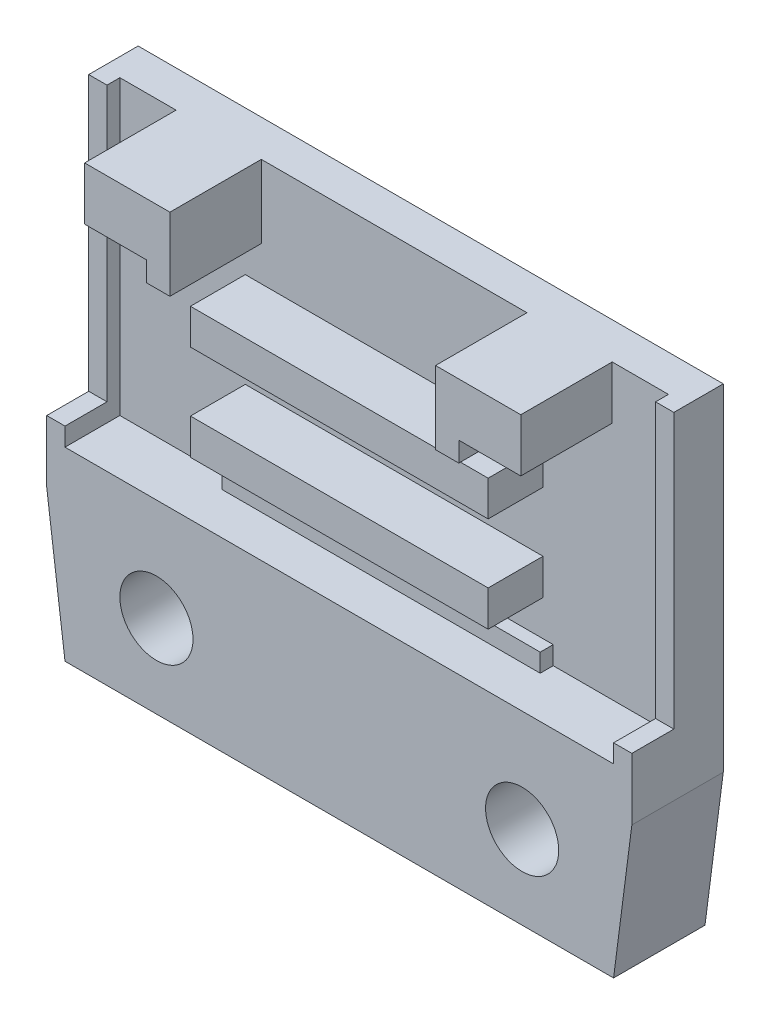
SolidWorks part; units mm, degrees
ref_plane "前视基准面" through (0, 0, 0) normal (0, 0, 1) x (1, 0, 0)
ref_plane "上视基准面" through (0, 0, 0) normal (0, 1, 0) x (1, 0, 0)
ref_plane "右视基准面" through (0, 0, 0) normal (1, 0, 0) x (0, 0, -1)
other "Configuration Table"
sketch "草图1" plane through (0, 0, 0) normal (0, 0, 1) x (1, 0, 0)
  line L1 (0, 0) -> (30, 0)
  line L2 (0, 0) -> (0, 15)
  line L3 (0, 15) -> (30, 15)
  line L4 (30, 0) -> (30, 15)
  dimension "D1" = 30
  dimension "D2" = 15
extrude "凸台-拉伸1" add sketch "草图1" along normal mid plane 2
sketch "草图2" plane through (0, 0, 1) normal (0, 0, 1) x (1, 0, 0)
  line L0 (25, 0) -> (25, -6.6)
  line L1 (0, 0) -> (30, 0) construction
  line L2 (30, 0) -> (30, 15) construction
  line L3 (30, 0) -> (30, -11.1397)
  line L4 (30, -11.1397) -> (0, -11.1397)
  line L5 (0, -11.1397) -> (0, 0)
  line L6 (15, -11.1397) -> (15, -4.661) construction
  line L7 (0, 0) -> (30, 0)
  circle A0 centre (25, -6.6) radius 2
  circle A1 centre (5, -6.6) radius 2
  dimension "D3" = 4
  dimension "D1" = 6.6
  dimension "D2" = 5
extrude "凸台-拉伸2" add sketch "草图2" along normal blind 3 and the other way blind 2
sketch "草图3" plane through (0, 0, 4) normal (0, 0, 1) x (1, 0, 0)
  line L0 (23.7, -1) -> (23.7, 0)
  line L1 (0, 0) -> (30, 0) construction
  line L2 (23.7, -1) -> (30, -1)
  line L3 (30, 0) -> (30, -11.1397) construction
  line L5 (23.7, 0) -> (30, 0)
  line L6 (30, 0) -> (30, -1)
  line L7 (15, 0) -> (15, 5.0746) construction
  line L8 (0, 0) -> (0, -1)
  line L9 (6.3, 0) -> (0, 0)
  line L10 (6.3, -1) -> (0, -1)
  line L11 (6.3, -1) -> (6.3, 0)
  dimension "D1" = 1
  dimension "D2" = 6.3
extrude "切除-拉伸1" cut sketch "草图3" against normal blind 3
sketch "草图4" plane through (30, 0, 0) normal (1, 0, 0) x (0, 0, -1)
  line L2 (-1.704, 0) -> (-1.704, 15)
  line L3 (-1.704, 15) -> (-1, 15)
  line L4 (-1, 15) -> (1, 15)
  line L5 (1, 15) -> (1, -3.391)
  line L6 (1, -11.1397) -> (1, 15) construction
  line L7 (1, -3.391) -> (-4, -3.391)
  line L8 (-4, -1) -> (-4, -11.1397) construction
  line L9 (-4, -3.391) -> (-4, 0)
  line L10 (-4, 0) -> (-1.704, 0)
  line L11 (-1, 0) -> (-4, 0) construction
extrude "凸台-拉伸3" add sketch "草图4" along normal blind 1
ref_plane "基准面1" through (15, 0, 0) normal (1, 0, 0) x (0, 0, -1)
sketch "草图5" plane through (0, 0, 4) normal (0, 0, 1) x (1, 0, 0)
  line L0 (31, -3.391) -> (30, -11.1397)
  line L1 (30, -11.1397) -> (30, -3.391)
  line L2 (30, -3.391) -> (31, -3.391)
extrude "凸台-拉伸4" add sketch "草图5" along direction (0, 0, -1) on the side against the normal up to surface (5 mm away)
mirror "镜向1" about plane through (15, 0, 0) normal (1, 0, 0) of "凸台-拉伸4", "凸台-拉伸3"
sketch "草图8" plane through (6.3, 0, 0) normal (-1, 0, 0) x (0, 0, 1)
  line L0 (1.7119, 0) -> (1.7119, -1)
  line L1 (1, 0) -> (4, 0) construction
  line L2 (1, -1) -> (4, -1) construction
  line L3 (1.7119, -1) -> (4, -1)
  line L4 (4, -1) -> (4, 0)
  line L5 (4, 0) -> (1.7119, 0)
extrude "切除-拉伸2" cut sketch "草图8" against normal up to next
sketch "草图9" plane through (0, 0, 1) normal (0, 0, 1) x (1, 0, 0)
  line L0 (3.0739, 15) -> (6.1478, 15)
  line L1 (30, 15) -> (0, 15) construction
  line L4 (3.0739, 11.937) -> (6.1478, 11.937)
  line L6 (15, 15) -> (15, 18.7793) construction
  line L12 (3.0739, 11.937) -> (3.0739, 15)
  line L13 (22.2627, 15) -> (23.8522, 15)
  line L14 (6.1478, 11.937) -> (6.2463, 11.937)
  line L15 (6.2463, 11.937) -> (6.2463, 11.0133)
  line L16 (6.2463, 11.0133) -> (7.7373, 11.0133)
  line L17 (7.7373, 11.0133) -> (7.7373, 15)
  line L18 (7.7373, 15) -> (6.1478, 15)
  line L19 (7.7373, 15) -> (6.1478, 15)
  line L20 (22.2627, 15) -> (23.8522, 15)
  line L21 (22.2627, 11.0133) -> (22.2627, 15)
  line L22 (23.7537, 11.0133) -> (22.2627, 11.0133)
  line L23 (23.7537, 11.937) -> (23.7537, 11.0133)
  line L24 (23.8522, 11.937) -> (23.7537, 11.937)
  line L25 (26.9261, 11.937) -> (26.9261, 15)
  line L26 (26.9261, 11.937) -> (23.8522, 11.937)
  line L27 (26.9261, 15) -> (23.8522, 15)
  line M19 (30, 15) -> (0, 15)
extrude "凸台-拉伸6" add sketch "草图9" along normal blind 5 contours L16 L17 L12 L4 L14 L15 M19 | L26 L25 L21 L22 L23 L24 M19
sketch "草图10" plane through (0, 0, 1) normal (0, 0, 1) x (1, 0, 0)
  line L0 (6.86, 1.9479) -> (23.14, 1.9479)
  line L1 (6.86, 3.9045) -> (23.14, 3.9045)
  line L2 (6.86, 7.1707) -> (23.14, 7.1707)
  line L3 (6.86, 9.1033) -> (23.14, 9.1033)
  line L4 (6.86, 9.1033) -> (6.86, 7.1707)
  line L5 (15, 9.1033) -> (15, 12.3733) construction
  line L6 (23.14, 9.1033) -> (23.14, 7.1707)
  line L7 (6.56, 7.5943) -> (6.56, 9.7057) construction
  line L8 (6.86, 3.9045) -> (6.86, 1.9479)
  line L10 (23.44, 3.2057) -> (23.44, 1.0943) construction
  line L11 (23.14, 3.9045) -> (23.14, 1.9479)
  dimension "D1" = 0.3
  dimension "D2" = 0.3
extrude "凸台-拉伸7" add sketch "草图10" along normal blind 3
sketch "草图11" plane through (0, 0, 6) normal (0, 0, 1) x (1, 0, 0)
  line L0 (23.8343, 11.8) -> (30, 11.8) construction
  line L2 (26.9261, 11.937) -> (26.9261, 15) construction
  line L3 (26.9261, 12.1) -> (23.5343, 12.1)
  line L4 (23.5343, 12.1) -> (23.5343, 11.0133)
  line L5 (23.7537, 11.0133) -> (22.2627, 11.0133) construction
  line L6 (23.5343, 11.0133) -> (23.8343, 11.0133)
  line L7 (23.8343, 10.1) -> (23.8343, 11.8) construction
  line L8 (23.7537, 11.0133) -> (23.7537, 11.937)
  line L9 (23.7537, 11.937) -> (26.9261, 11.937)
  line L10 (26.9261, 11.937) -> (23.7537, 11.937) construction
  line L12 (15, 15) -> (15, 19.17) construction
  line L13 (22.2627, 15) -> (7.7373, 15) construction
  line L14 (6.2463, 11.937) -> (3.0739, 11.937)
  line L15 (6.2463, 11.0133) -> (6.2463, 11.937)
  line L16 (6.4657, 11.0133) -> (6.1657, 11.0133)
  line L17 (6.4657, 12.1) -> (6.4657, 11.0133)
  line L18 (3.0739, 12.1) -> (6.4657, 12.1)
  line L19 (26.9261, 12.1) -> (26.9261, 11.937)
  line L20 (3.0739, 11.937) -> (3.0739, 12.1)
  line M4 (23.7537, 11.937) -> (26.9261, 11.937)
  line M5 (26.9261, 11.937) -> (26.9261, 15)
  line M8 (22.2627, 11.0133) -> (23.7537, 11.0133)
  line M9 (23.7537, 11.0133) -> (23.7537, 11.937)
  dimension "D1" = 0.3
  dimension "D2" = 0.3
extrude "切除-拉伸3" cut sketch "草图11" against normal blind 5 contours L20 L14 L15 L16 L17 L18 | L3 L4 M8 M9 M4 M5
